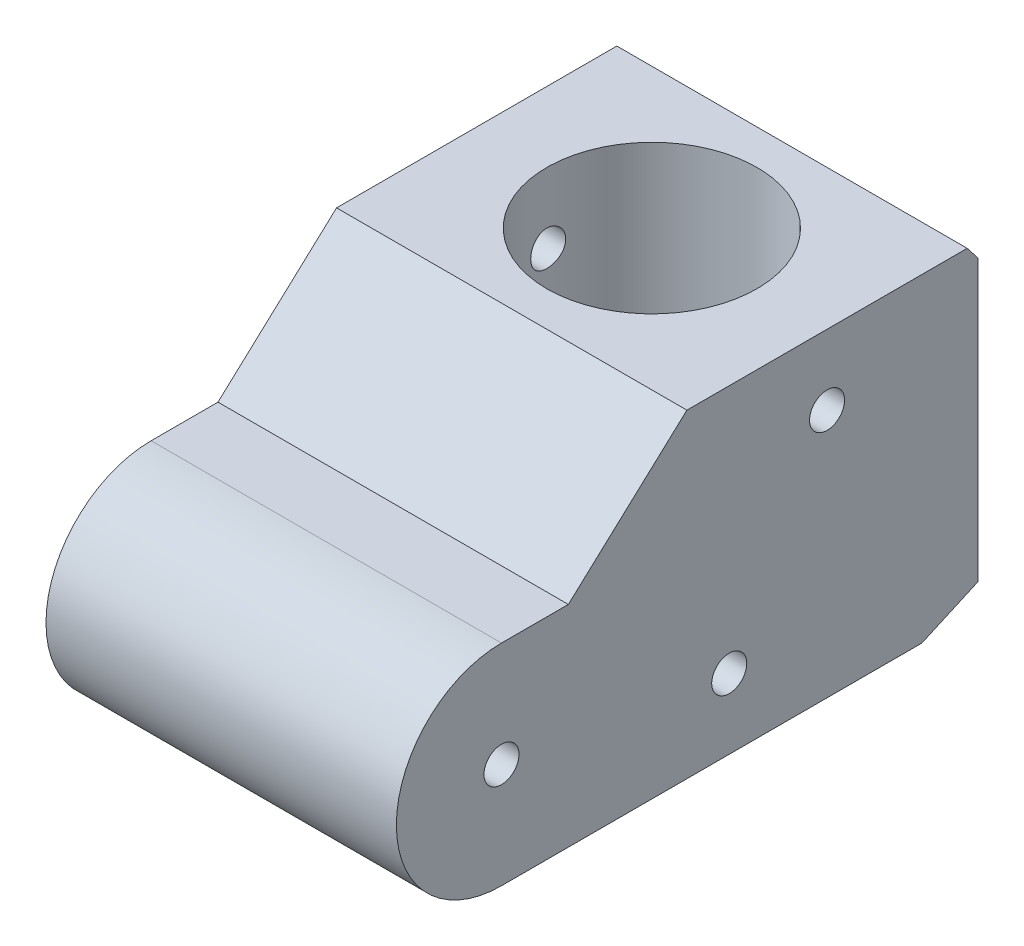
SolidWorks part; units mm, degrees
ref_plane "Front Plane" through (0, 0, 0) normal (0, 0, 1) x (1, 0, 0)
ref_plane "Top Plane" through (0, 0, 0) normal (0, 1, 0) x (1, 0, 0)
ref_plane "Right Plane" through (0, 0, 0) normal (1, 0, 0) x (0, 0, -1)
sketch "Sketch1" plane through (0, 0, 0) normal (1, 0, 0) x (0, 0, -1)
  line L1 (-60, 30) -> (60, 30)
  line L2 (-60, 30) -> (-60, -30)
  line L3 (-60, -30) -> (60, -30)
  line L4 (60, 30) -> (60, -30)
  line L5 (-60, 30) -> (60, -30) construction
  line L6 (-60, -30) -> (60, 30) construction
  point P0 (0, 0)
  dimension "D1" = 120
  dimension "D2" = 60
extrude "Boss-Extrude1" add sketch "Sketch1" against normal blind 100
sketch "Sketch2" plane through (0, -30, 0) normal (0, -1, 0) x (1, 0, 0)
  circle A0 centre (-50, -5) radius 40
  dimension "D1" = 80
extrude "Cut-Extrude1" cut sketch "Sketch2" against normal blind 30
sketch "Sketch3" plane through (0, 0, 0) normal (1, 0, 0) x (0, 0, -1)
  line L0 (-35, -30) -> (45, -30) construction
  circle A0 centre (5, -10) radius 5
  dimension "D1" = 10
  dimension "D2" = 20
extrude "Cut-Extrude2" cut sketch "Sketch3" against normal through all
sketch "Sketch4" plane through (0, 0, 0) normal (1, 0, 0) x (0, 0, -1)
  line L0 (-60, 30) -> (-60, -30)
  line L1 (60, 30) -> (60, -30)
  line L2 (60, -30) -> (76, -22.8367)
  line L3 (76, -22.8367) -> (76, 57.1633)
  line L5 (-7.0788, 61.103) -> (-40.9156, 30)
  line L6 (76, 57.1633) -> (72.9212, 61.103)
  line L7 (72.9212, 61.103) -> (-7.0788, 61.103)
  line L8 (60, 30) -> (-60, 30) construction
  line L9 (-40.9156, 30) -> (60, 30)
  arc A0 (-60, -30) -> (-60, 30) centre (-60, 0) cw
  point P11 (68, -26.4183)
  dimension "D1" = 5
  dimension "D2" = 8
  dimension "D3" = 80
  dimension "D4" = 80
extrude "Boss-Extrude2" add sketch "Sketch4" against normal blind 100
sketch "Sketch9" plane through (0, 61.103, 0) normal (0, 1, 0) x (1, 0, 0)
  circle A0 centre (-50, 32.9212) radius 30
  dimension "D1" = 60
extrude "Cut-Extrude6" cut sketch "Sketch9" against normal blind 50
sketch "Sketch5" plane through (0, 0, 0) normal (1, 0, 0) x (0, 0, -1)
  line L0 (-60, 0) -> (-55, 0) construction
  line L1 (62.9212, 61.103) -> (2.9212, 61.103) construction
  circle A0 centre (-60, 0) radius 5
  circle A2 centre (32.9212, 41.103) radius 5
  dimension "D1" = 10
  dimension "D2" = 20
  dimension "D3" = 10
extrude "Cut-Extrude3" cut sketch "Sketch5" against normal blind 100
